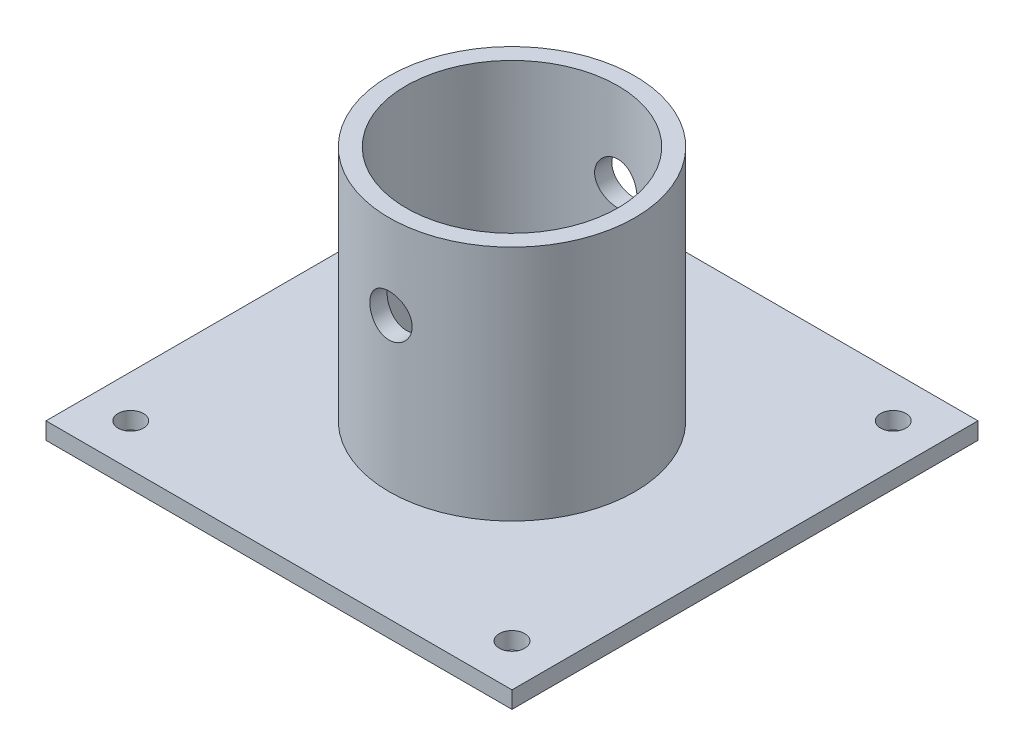
SolidWorks part; units mm, degrees
material "AISI 316 Отожженная нержавеющая сталь. полоса (SS)"
ref_plane "Спереди XY" through (0, 0, 0) normal (0, 0, 1) x (1, 0, 0)
ref_plane "Сверху XZ" through (0, 0, 0) normal (0, 1, 0) x (1, 0, 0)
ref_plane "Справа ZY" through (0, 0, 0) normal (1, 0, 0) x (0, 0, -1)
sketch "Эскиз1" plane through (0, 0, 0) normal (0, 1, 0) x (1, 0, 0)
  line L1 (27.5, -27.5) -> (-27.5, -27.5)
  line L2 (27.5, -27.5) -> (27.5, 27.5)
  line L3 (27.5, 27.5) -> (-27.5, 27.5)
  line L4 (-27.5, -27.5) -> (-27.5, 27.5)
  line L5 (27.5, -27.5) -> (-27.5, 27.5) construction
  line L6 (27.5, 27.5) -> (-27.5, -27.5) construction
  circle A0 centre (0, 0) radius 12.5
  point P0 (0, 0)
  dimension "D2" = 25
  dimension "D1" = 55
extrude "Бобышка-Вытянуть1" add sketch "Эскиз1" along normal blind 2
sketch "Эскиз2" plane through (0, 0, 0) normal (0, -1, 0) x (1, 0, 0)
  circle A0 centre (0, 0) radius 12.5 construction
  circle A1 centre (0, 0) radius 12.5
extrude "Вытянуть-Тонкостенный1" add sketch "Эскиз2" against normal blind 30 thin
sketch "Эскиз3" plane through (0, 0, 0) normal (0, 0, 1) x (1, 0, 0)
  line L0 (0, 46.6859) -> (0, -24.8732) construction
  line L1 (-27.5, 0) -> (27.5, 0) construction
  circle A0 centre (0, 20) radius 2.5
  dimension "D1" = 5
  dimension "D2" = 20
extrude "Вырез-Вытянуть1" cut sketch "Эскиз3" against normal through all both and the other way through all
sketch "Эскиз4" plane through (0, 0, 0) normal (0, 1, 0) x (1, 0, 0)
  line L0 (27.5, 27.5) -> (-27.5, 27.5) construction
  line L1 (-27.5, 27.5) -> (-27.5, -27.5) construction
  circle A0 centre (-22.5, 22.5) radius 1.5
  circle A1 centre (22.5, 22.5) radius 1.5
  circle A2 centre (22.5, -22.5) radius 1.5
  circle A3 centre (-22.5, -22.5) radius 1.5
  point P15 (0, 0)
  dimension "D3" = 3
  dimension "D1" = 5
  dimension "D2" = 5
  dimension "D4" = 4
extrude "Вырез-Вытянуть7" cut sketch "Эскиз4" against normal through all and the other way through all
